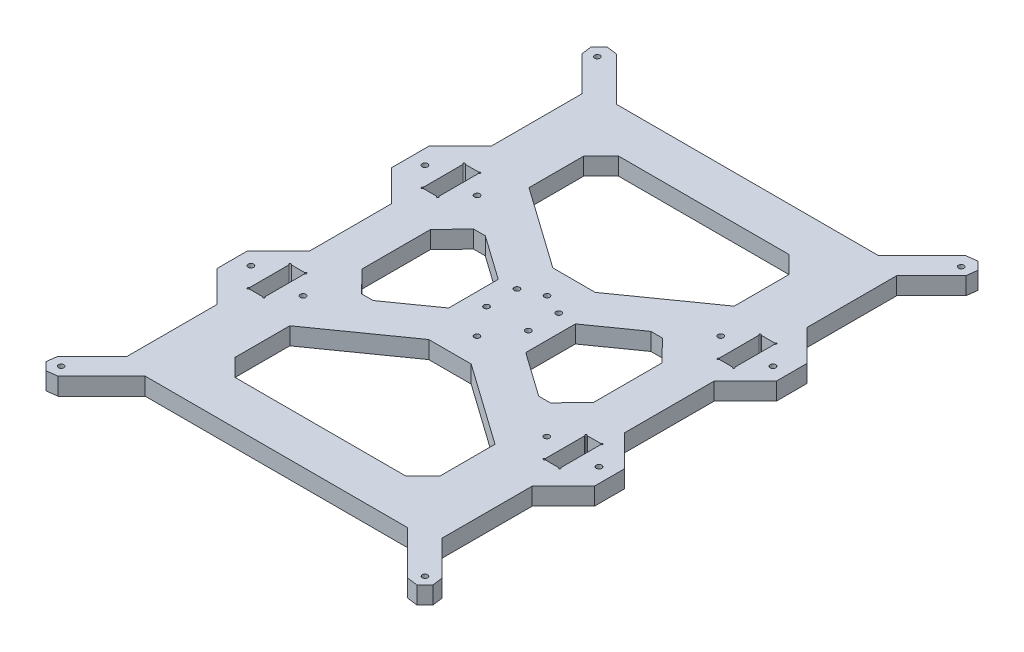
SolidWorks part; units mm, degrees
ref_plane "Alzado" through (0, 0, 0) normal (0, 0, 1) x (1, 0, 0)
ref_plane "Planta" through (0, 0, 0) normal (0, 1, 0) x (1, 0, 0)
ref_plane "Vista lateral" through (0, 0, 0) normal (1, 0, 0) x (0, 0, -1)
sketch "Croquis1" plane through (0, 0, 0) normal (0, 1, 0) x (1, 0, 0)
  line L0 (-39.0365, 19.6293) -> (-39.0365, -19.6293)
  line L1 (-59.0494, 39.007) -> (-56.1522, 39.007) construction
  line L2 (-83.7317, 156.5575) -> (-79.1583, 161.1309)
  line L3 (-80.9341, 58.992) -> (-80.9341, 60.9895)
  line L4 (-83.7317, 156.5575) -> (-82.9315, 150.4313)
  line L5 (-82.9315, 150.4313) -> (-63.0494, 130.5491)
  line L6 (-63.0494, 130.5491) -> (-63.0494, 78.8741)
  line L7 (-63.0494, 78.8741) -> (-72.9315, 68.992)
  line L8 (-63.0494, 21.1259) -> (-63.0494, -25.6817)
  line L9 (-80.9341, -43.5663) -> (-80.9341, -60.9895)
  line L10 (135.7344, 58.992) -> (135.7344, 60.9875)
  line L11 (-31.543, 100.14) -> (-31.543, 68.7002)
  line L12 (-31.543, 100.14) -> (-21.543, 110.14)
  line L13 (-57.6008, -37.9512) -> (-57.6008, -62.0512) construction
  line L14 (135.7344, -43.5683) -> (135.7344, -60.9875)
  line L15 (-61.2348, -37.9512) -> (-53.9668, -37.9512)
  line L16 (-79.1583, 161.1309) -> (-73.032, 160.3308)
  line L17 (-80.9341, 58.992) -> (-80.9341, 39.0105)
  line L20 (112.3992, -37.9512) -> (112.3992, -62.0512) construction
  line L21 (108.7652, -37.9512) -> (116.0332, -37.9512)
  line L22 (-72.9315, -35.5638) -> (-80.9341, -43.5663)
  line L23 (-63.0494, 21.1259) -> (-72.9315, 31.008)
  line L24 (127.8305, 160.3308) -> (102.7925, 135.2928)
  line L25 (74.963, 32.2218) -> (49.5544, 14.253)
  line L26 (81.6423, 32.2218) -> (74.963, 32.2218)
  line L27 (-31.543, 68.7002) -> (15.2174, 35.6316)
  line L28 (15.2174, 35.6316) -> (39.581, 35.6316)
  line L29 (93.8349, 19.6293) -> (81.6423, 32.2218)
  line L30 (86.3414, 68.7002) -> (39.581, 35.6316)
  line L31 (-47.9941, 135.2928) -> (102.7925, 135.2928)
  line L32 (117.8478, 25.6817) -> (127.73, 35.5638)
  line L33 (-62.1008, -61.1852) -> (-62.1008, -38.8172)
  line L34 (133.9567, 161.1309) -> (127.8305, 160.3308)
  line L35 (107.8992, -61.1852) -> (107.8992, -38.8172)
  line L36 (-39.0365, 19.6293) -> (-26.8439, 32.2218)
  line L37 (-26.8439, 32.2218) -> (-20.1646, 32.2218)
  line L38 (-20.1646, 32.2218) -> (5.244, 14.253)
  line L39 (116.8992, -38.8172) -> (116.8992, -61.1852)
  line L40 (86.3414, 100.14) -> (76.3414, 110.14)
  line L41 (86.3414, 100.14) -> (86.3414, 68.7002)
  line L42 (-57.6008, 62.007) -> (-57.6008, 37.907) construction
  line L43 (117.8478, 25.6817) -> (117.8478, -25.6817)
  line L44 (117.8478, 78.8741) -> (127.73, 68.992)
  line L45 (117.8478, 130.5491) -> (117.8478, 78.8741)
  line L46 (137.73, 150.4313) -> (117.8478, 130.5491)
  line L47 (138.5301, 156.5575) -> (137.73, 150.4313)
  line L48 (138.5301, 156.5575) -> (133.9567, 161.1309)
  line L49 (93.8349, 19.6293) -> (93.8349, -19.6293)
  line L50 (-21.543, 110.14) -> (76.3414, 110.14)
  line L51 (135.7344, 58.992) -> (135.7344, 43.5683)
  line L57 (112.3992, 62.007) -> (112.3992, 37.907) construction
  line L58 (108.7652, 62.007) -> (116.0332, 62.007)
  line L59 (-73.032, -160.3308) -> (-47.9941, -135.2928)
  line L60 (-21.543, -110.14) -> (76.3414, -110.14)
  line L61 (-73.032, 160.3308) -> (-47.9941, 135.2928)
  line L62 (138.5301, -156.5575) -> (133.9567, -161.1309)
  line L63 (138.5301, -156.5575) -> (137.73, -150.4313)
  line L64 (137.73, -150.4313) -> (117.8478, -130.5491)
  line L65 (117.8478, -130.5491) -> (117.8478, -78.8741)
  line L66 (117.8478, -78.8741) -> (127.73, -68.992)
  line L67 (86.3414, -100.14) -> (86.3414, -68.7002)
  line L68 (86.3414, -100.14) -> (76.3414, -110.14)
  line L70 (-20.1646, -32.2218) -> (5.244, -14.253)
  line L71 (-26.8439, -32.2218) -> (-20.1646, -32.2218)
  line L72 (-53.1008, -38.8172) -> (-53.1008, -61.1852)
  line L73 (-53.9668, -62.0512) -> (-61.2348, -62.0512)
  line L74 (-39.0365, -19.6293) -> (-26.8439, -32.2218)
  line L76 (133.9567, -161.1309) -> (127.8305, -160.3308)
  line L78 (117.8478, -25.6817) -> (127.73, -35.5638)
  line L79 (-47.9941, -135.2928) -> (102.7925, -135.2928)
  line L80 (86.3414, -68.7002) -> (39.581, -35.6316)
  line L81 (93.8349, -19.6293) -> (81.6423, -32.2218)
  line L82 (15.2174, -35.6316) -> (39.581, -35.6316)
  line L83 (-31.543, -68.7002) -> (15.2174, -35.6316)
  line L84 (81.6423, -32.2218) -> (74.963, -32.2218)
  line L85 (74.963, -32.2218) -> (49.5544, -14.253)
  line L86 (127.8305, -160.3308) -> (102.7925, -135.2928)
  line L87 (-63.0494, -25.6817) -> (-72.9315, -35.5638)
  line L91 (-79.1583, -161.1309) -> (-73.032, -160.3308)
  line L92 (107.8992, 38.7731) -> (107.8992, 61.141)
  line L93 (116.8992, 61.141) -> (116.8992, 38.7731)
  line L94 (-31.543, -100.14) -> (-21.543, -110.14)
  line L95 (-31.543, -100.14) -> (-31.543, -68.7002)
  line L96 (-63.0494, -78.8741) -> (-72.9315, -68.992)
  line L97 (-63.0494, -130.5491) -> (-63.0494, -78.8741)
  line L98 (-82.9315, -150.4313) -> (-63.0494, -130.5491)
  line L99 (-83.7317, -156.5575) -> (-82.9315, -150.4313)
  line L100 (-83.7317, -156.5575) -> (-79.1583, -161.1309)
  line L267 (27.3992, 135.2928) -> (27.3992, 66.9001) construction
  line L268 (49.5544, 14.253) -> (49.5544, -14.253)
  line L269 (26.7356, 18.7305) -> (34.742, 35.6316) construction
  line L270 (5.244, 14.253) -> (5.244, -14.253)
  line L271 (27.3992, 35.6316) -> (27.3992, 18.5813) construction
  line L272 (27.3992, -18.5813) -> (27.3992, -135.2928) construction
  line L273 (20.0564, 35.6316) -> (28.0628, 18.7305) construction
  line L274 (-57.6008, 62.007) -> (-57.6008, 37.907) construction
  line L275 (-72.9315, 68.992) -> (-80.9341, 60.9895)
  line L276 (-61.2348, 62.007) -> (-53.9668, 62.007)
  line L277 (-62.1008, 38.7731) -> (-62.1008, 61.141)
  line L278 (-53.1008, 61.141) -> (-53.1008, 38.7731)
  line L279 (-53.9668, 37.907) -> (-61.2348, 37.907)
  line L280 (-72.9315, -68.992) -> (-80.9341, -60.9895)
  line L281 (127.73, 68.992) -> (135.7344, 60.9875)
  line L282 (116.0332, 37.907) -> (108.7652, 37.907)
  line L284 (-72.9315, 31.008) -> (-80.9341, 39.0105)
  line L285 (116.0332, -62.0512) -> (108.7652, -62.0512)
  line L288 (127.73, 35.5638) -> (135.7344, 43.5683)
  line L289 (127.73, -35.5638) -> (135.7344, -43.5683)
  line L290 (127.73, -68.992) -> (135.7344, -60.9875)
  circle A0 centre (-72.6009, -50.0012) radius 1.6
  arc A1 (-62.1008, -38.8172) -> (-62.3508, -38.3842) centre (-62.6008, -38.8172) ccw
  arc A2 (-61.6678, -37.7012) -> (-62.3508, -38.3842) centre (-62.1008, -37.9512) ccw
  arc A3 (-61.6678, -37.7012) -> (-61.2348, -37.9512) centre (-61.2348, -37.4512) ccw
  circle A4 centre (-72.6009, 49.957) radius 1.6
  circle A5 centre (97.3991, -50.0012) radius 1.6
  circle A6 centre (-77.1008, 153.5) radius 1.55
  arc A7 (107.8992, -38.8172) -> (107.6492, -38.3842) centre (107.3992, -38.8172) ccw
  circle A8 centre (131.8992, 153.5) radius 1.55
  arc A9 (108.3322, -37.7012) -> (107.6492, -38.3842) centre (107.8992, -37.9512) ccw
  arc A10 (108.3322, -37.7012) -> (108.7652, -37.9512) centre (108.7652, -37.4512) ccw
  arc A11 (116.0332, -37.9512) -> (116.4662, -37.7012) centre (116.0332, -37.4512) ccw
  arc A12 (117.1492, -38.3842) -> (116.4662, -37.7012) centre (116.8992, -37.9512) ccw
  arc A13 (-62.1008, 61.141) -> (-62.3508, 61.574) centre (-62.6008, 61.141) ccw
  circle A14 centre (97.3991, 49.957) radius 1.6
  circle A15 centre (27.3992, 20.1313) radius 1.55
  arc A16 (107.8992, 61.141) -> (107.6492, 61.574) centre (107.3992, 61.141) ccw
  arc A17 (-53.9668, -37.9512) -> (-53.5338, -37.7012) centre (-53.9668, -37.4512) ccw
  circle A18 centre (27.3992, -20.1313) radius 1.55
  arc A19 (-52.8508, -38.3842) -> (-53.5338, -37.7012) centre (-53.1008, -37.9512) ccw
  circle A24 centre (131.8992, -154.5) radius 1.55
  circle A26 centre (-77.1008, -154.5) radius 1.55
  arc A28 (-61.6678, 62.257) -> (-62.3508, 61.574) centre (-62.1008, 62.007) ccw
  arc A29 (108.3322, 62.257) -> (107.6492, 61.574) centre (107.8992, 62.007) ccw
  arc A30 (-61.6678, 62.257) -> (-61.2348, 62.007) centre (-61.2348, 62.507) ccw
  arc A31 (108.3322, 62.257) -> (108.7652, 62.007) centre (108.7652, 62.507) ccw
  arc A32 (116.0332, 62.007) -> (116.4662, 62.257) centre (116.0332, 62.507) ccw
  arc A33 (117.1492, 61.574) -> (116.4662, 62.257) centre (116.8992, 62.007) ccw
  circle A272 centre (39.3992, 14.8687) radius 1.6
  arc A273 (-53.9668, 62.007) -> (-53.5338, 62.257) centre (-53.9668, 62.507) ccw
  circle A274 centre (15.3992, 14.8687) radius 1.6
  circle A275 centre (39.3992, -2.6313) radius 1.6
  circle A276 centre (15.3992, -2.6313) radius 1.6
  arc A277 (-52.8508, 61.574) -> (-53.5338, 62.257) centre (-53.1008, 62.007) ccw
  arc A278 (-52.8508, 61.574) -> (-53.1008, 61.141) centre (-52.6008, 61.141) ccw
  arc A279 (-53.1008, 38.7731) -> (-52.8508, 38.34) centre (-52.6008, 38.7731) ccw
  arc A280 (-53.5338, 37.657) -> (-52.8508, 38.34) centre (-53.1008, 37.907) ccw
  arc A281 (-53.5338, 37.657) -> (-53.9668, 37.907) centre (-53.9668, 37.407) ccw
  arc A282 (-61.2348, 37.907) -> (-61.6678, 37.657) centre (-61.2348, 37.407) ccw
  arc A283 (-62.3508, 38.3401) -> (-61.6678, 37.657) centre (-62.1008, 37.907) ccw
  arc A284 (-62.3508, 38.3401) -> (-62.1008, 38.7731) centre (-62.6008, 38.7731) ccw
  circle A285 centre (-42.6009, 49.957) radius 1.6
  arc A286 (-52.8508, -38.3842) -> (-53.1008, -38.8172) centre (-52.6008, -38.8172) ccw
  arc A287 (-53.1008, -61.1852) -> (-52.8508, -61.6182) centre (-52.6008, -61.1852) ccw
  arc A288 (-53.5338, -62.3012) -> (-52.8508, -61.6182) centre (-53.1008, -62.0512) ccw
  arc A289 (-53.5338, -62.3012) -> (-53.9668, -62.0512) centre (-53.9668, -62.5512) ccw
  arc A290 (-61.2348, -62.0512) -> (-61.6678, -62.3012) centre (-61.2348, -62.5512) ccw
  arc A291 (-62.3508, -61.6182) -> (-61.6678, -62.3012) centre (-62.1008, -62.0512) ccw
  arc A292 (-62.3508, -61.6182) -> (-62.1008, -61.1852) centre (-62.6008, -61.1852) ccw
  circle A293 centre (-42.6009, -50.0012) radius 1.6
  arc A294 (117.1492, 61.574) -> (116.8992, 61.141) centre (117.3992, 61.141) ccw
  arc A295 (116.8992, 38.7731) -> (117.1492, 38.34) centre (117.3992, 38.7731) ccw
  arc A296 (116.4662, 37.657) -> (117.1492, 38.34) centre (116.8992, 37.907) ccw
  arc A297 (116.4662, 37.657) -> (116.0332, 37.907) centre (116.0332, 37.407) ccw
  arc A298 (108.7652, 37.907) -> (108.3322, 37.657) centre (108.7652, 37.407) ccw
  arc A299 (107.6492, 38.3401) -> (108.3322, 37.657) centre (107.8992, 37.907) ccw
  arc A300 (107.6492, 38.3401) -> (107.8992, 38.7731) centre (107.3992, 38.7731) ccw
  circle A301 centre (127.3991, 49.957) radius 1.6
  arc A302 (117.1492, -38.3842) -> (116.8992, -38.8172) centre (117.3992, -38.8172) ccw
  arc A303 (116.8992, -61.1852) -> (117.1492, -61.6182) centre (117.3992, -61.1852) ccw
  arc A304 (116.4662, -62.3012) -> (117.1492, -61.6182) centre (116.8992, -62.0512) ccw
  arc A305 (116.4662, -62.3012) -> (116.0332, -62.0512) centre (116.0332, -62.5512) ccw
  arc A306 (108.7652, -62.0512) -> (108.3322, -62.3012) centre (108.7652, -62.5512) ccw
  arc A307 (107.6492, -61.6182) -> (108.3322, -62.3012) centre (107.8992, -62.0512) ccw
  arc A308 (107.6492, -61.6182) -> (107.8992, -61.1852) centre (107.3992, -61.1852) ccw
  circle A309 centre (127.3991, -50.0012) radius 1.6
  point P1 (-31.543, -110.14)
  point P8 (-63.0494, 0)
  point P23 (-81.445, 158.8442)
  point P62 (-39.0365, 0)
  point P65 (27.3992, 110.14)
  point P73 (27.3992, 135.2928)
  point P74 (27.3992, 35.6316)
  point P89 (86.3414, 110.14)
  point P90 (136.2434, 158.8442)
  point P127 (-31.543, 110.14)
  point P160 (93.8349, 0)
  point P167 (117.8478, 0)
  point P189 (-39.0365, 0)
  point P192 (136.2434, -158.8442)
  point P193 (86.3414, -110.14)
  point P194 (27.3992, -35.6316)
  point P195 (27.3992, -135.2928)
  point P196 (27.3992, -110.14)
  point P197 (-81.445, -158.8442)
  dimension "D1" = 308
  dimension "D8" = 3.1
  dimension "D2" = 308
extrude "Saliente-Extruir1" add sketch "Croquis1" along normal blind 10
